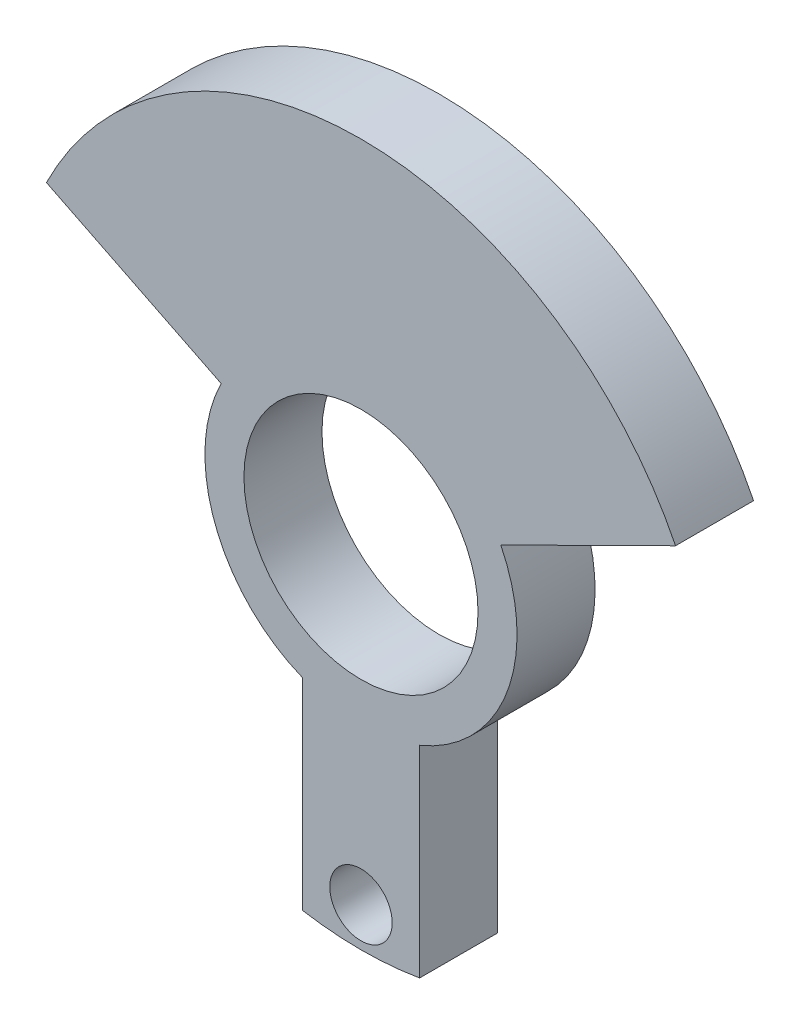
SolidWorks part; units mm, degrees
ref_plane "Front Plane" through (0, 0, 0) normal (0, 0, 1) x (1, 0, 0)
ref_plane "Top Plane" through (0, 0, 0) normal (0, 1, 0) x (1, 0, 0)
ref_plane "Right Plane" through (0, 0, 0) normal (1, 0, 0) x (0, 0, -1)
sketch "Sketch1" plane through (0, 0, 0) normal (0, 0, 1) x (1, 0, 0)
  line L0 (-40.3113, 20) -> (-17.9161, 8.8889)
  line L1 (-7.5128, -18.5353) -> (-7.5128, -44.3684)
  line L2 (0, 54.4193) -> (0, -88.5191) construction
  line L3 (7.5128, -18.5353) -> (7.5128, -44.3684)
  line L4 (40.3113, 20) -> (17.9161, 8.8889)
  arc A0 (40.3113, 20) -> (-40.3113, 20) centre (0, 0) ccw
  circle A1 centre (0, 0) radius 15
  arc A2 (-17.9161, 8.8889) -> (-7.5128, -18.5353) centre (0, 0) ccw
  arc A3 (-7.5128, -44.3684) -> (7.5128, -44.3684) centre (0, 0) ccw
  arc A4 (7.5128, -18.5353) -> (17.9161, 8.8889) centre (0, 0) ccw
extrude "Boss-Extrude1" add sketch "Sketch1" along normal mid plane 10
sketch "Sketch2" plane through (0, 0, 5) normal (0, 0, 1) x (1, 0, 0)
  line L0 (0, 0) -> (0, -40) construction
  circle A1 centre (0, -40) radius 4
extrude "Cut-Extrude1" cut sketch "Sketch2" against normal through all
